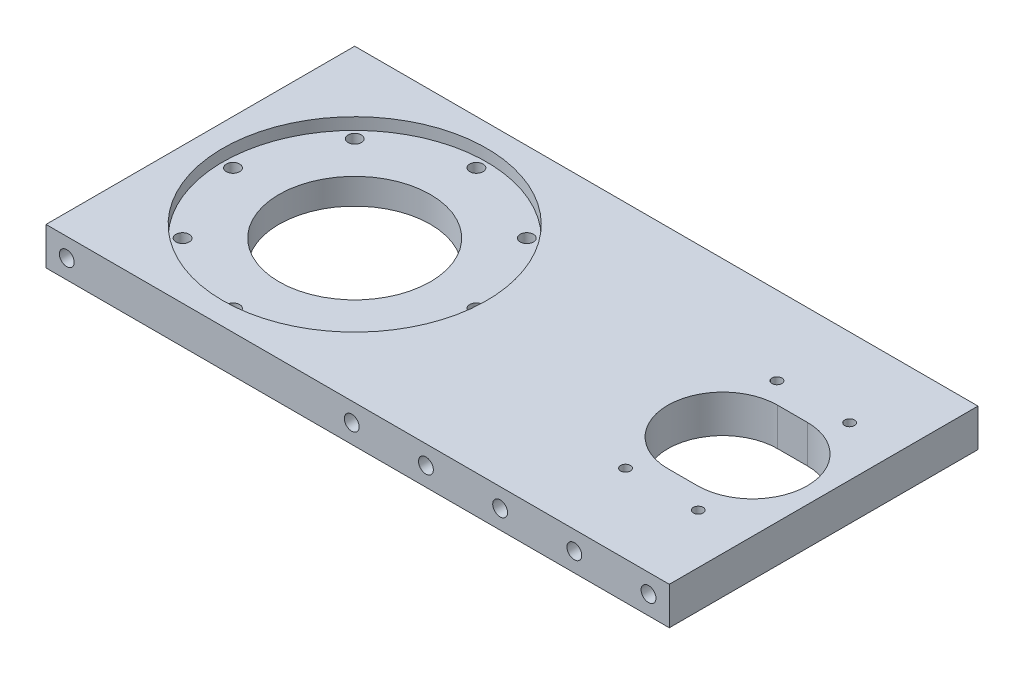
SolidWorks part; units mm, degrees
material "1060 合金"
ref_plane "前视基准面" through (0, 0, 0) normal (0, 0, 1) x (1, 0, 0)
ref_plane "上视基准面" through (0, 0, 0) normal (0, 1, 0) x (1, 0, 0)
ref_plane "右视基准面" through (0, 0, 0) normal (1, 0, 0) x (0, 0, -1)
sketch "草图1" plane through (0, 0, 0) normal (0, 1, 0) x (1, 0, 0)
  line L0 (0, 0) -> (170, 0) construction
  line L1 (170, 31.93) -> (170, -31.93)
  line L2 (15.8391, 73.3084) -> (162.1119, 41.7045)
  line L3 (15.8391, -73.3084) -> (162.1119, -41.7045)
  arc A0 (15.8391, 73.3084) -> (15.8391, -73.3084) centre (0, 0) ccw
  arc A1 (162.1119, -41.7045) -> (170, -31.93) centre (160, -31.93) ccw
  arc A2 (170, 31.93) -> (162.1119, 41.7045) centre (160, 31.93) ccw
  point P6 (170, 0)
  dimension "D1" = 150
  dimension "D4" = 20
  dimension "D5" = 20
  dimension "D2" = 170
  dimension "D3" = 63.86
extrude "凸台-拉伸1" add sketch "草图1" along normal blind 30
sketch "草图2" plane through (0, 30, 0) normal (0, 1, 0) x (1, 0, 0)
  circle A0 centre (0, 0) radius 44.45
  dimension "D1" = 88.9
extrude "切除-拉伸1" cut sketch "草图2" against normal blind 4
sketch "草图3" plane through (0, 26, 0) normal (0, 1, 0) x (1, 0, 0)
  line L0 (0, 0) -> (0, 90.3276) construction
  circle A0 centre (0, 0) radius 25.5
  circle A1 centre (0, 41) radius 2.25
  circle A2 centre (28.9914, 28.9914) radius 2.25
  circle A3 centre (41, 0) radius 2.25
  circle A4 centre (28.9914, -28.9914) radius 2.25
  circle A5 centre (0, -41) radius 2.25
  circle A6 centre (-28.9914, -28.9914) radius 2.25
  circle A7 centre (-41, 0) radius 2.25
  circle A8 centre (-28.9914, 28.9914) radius 2.25
  dimension "D1" = 51
  dimension "D3" = 4.5
  dimension "D2" = 41
  dimension "D4" = 8
extrude "切除-拉伸2" cut sketch "草图3" against normal through all contours A2 | A3 | A4 | A5 | A6 | A7 | A8 | A1 | A0
sketch "草图4" plane through (0, 30, 0) normal (0, 1, 0) x (1, 0, 0)
  line L0 (0, 0) -> (134, 0) construction
  line L1 (124, 18.5) -> (134, 18.5)
  line L2 (124, -18.5) -> (134, -18.5)
  arc A0 (134, -18.5) -> (134, 18.5) centre (134, 0) ccw
  arc A1 (124, 18.5) -> (124, -18.5) centre (124, 0) ccw
  dimension "D2" = 37
  dimension "D3" = 37
  dimension "D1" = 134
  dimension "D4" = 10
extrude "切除-拉伸3" cut sketch "草图4" against normal through all
sketch "草图5" plane through (0, 30, 0) normal (0, 1, 0) x (1, 0, 0)
  arc A0 (134, -18.5) -> (134, 18.5) centre (134, 0) ccw construction
  arc A1 (124, 18.5) -> (124, -18.5) centre (124, 0) ccw construction
  arc A2 (134, -18.5) -> (134, 18.5) centre (134, 0) ccw construction
  arc A3 (124, 18.5) -> (124, -18.5) centre (124, 0) ccw construction
  circle A4 centre (116.75, 25.5) radius 1.65
  circle A5 centre (141.25, 25.5) radius 1.65
  circle A6 centre (141.25, -25.5) radius 1.65
  circle A7 centre (116.75, -25.5) radius 1.65
  dimension "D1" = 3.3
  dimension "D2" = 3.3
  dimension "D3" = 3.3
  dimension "D4" = 3.3
  dimension "D7" = 25.5
  dimension "D5" = 7.25
  dimension "D6" = 25.5
  dimension "D8" = 7.25
  dimension "D9" = 7.25
extrude "切除-拉伸4" cut sketch "草图5" against normal through all
sketch "草图6" plane through (0, 30, 0) normal (0, 1, 0) x (1, 0, 0)
  line L0 (158, 42.5929) -> (158, -42.5929) construction
  line L2 (-52, 54.0463) -> (-52, -54.0463) construction
  line L6 (162.1119, 41.7045) -> (15.8391, 73.3084) construction
  line L7 (15.8391, -73.3084) -> (162.1119, -41.7045) construction
  line L8 (-52, 95) -> (-52, -95)
  line L9 (158, 95) -> (158, -95)
  line L10 (-52, 95) -> (158, 95)
  line L11 (-52, -95) -> (158, -95)
  line L15 (162.1119, 41.7045) -> (15.8391, 73.3084)
  line L16 (15.8391, -73.3084) -> (162.1119, -41.7045)
  line L17 (170, -31.93) -> (170, 31.93)
  line L18 (162.1119, 41.7045) -> (15.8391, 73.3084)
  line L19 (15.8391, -73.3084) -> (162.1119, -41.7045)
  line L20 (170, -31.93) -> (170, 31.93)
  arc A0 (15.8391, 73.3084) -> (15.8391, -73.3084) centre (0, 0) ccw construction
  arc A6 (170, 31.93) -> (162.1119, 41.7045) centre (160, 31.93) ccw
  arc A7 (15.8391, 73.3084) -> (15.8391, -73.3084) centre (0, 0) ccw
  arc A8 (162.1119, -41.7045) -> (170, -31.93) centre (160, -31.93) ccw
  arc A9 (170, 31.93) -> (162.1119, 41.7045) centre (160, 31.93) ccw
  arc A10 (15.8391, 73.3084) -> (15.8391, -73.3084) centre (0, 0) ccw
  arc A11 (162.1119, -41.7045) -> (170, -31.93) centre (160, -31.93) ccw
  point P8 (-52, 0)
  point P13 (158, 0)
  line M26 (162.1119, 41.7045) -> (15.8391, 73.3084)
  arc M27 (15.8391, 73.3084) -> (15.8391, -73.3084) centre (0, 0) ccw
  line M28 (15.8391, -73.3084) -> (162.1119, -41.7045)
  dimension "D3" = 190
  dimension "D1" = 210
  dimension "D2" = 52
  dimension "D4" = 190
  dimension "D5" = 0
extrude "凸台-拉伸2" add sketch "草图6" against normal blind 30 contours L10 L8 L9 M27 M26 | L8 L11 L9 M28 M27
sketch "草图7" plane through (0, 30, 0) normal (0, 1, 0) x (1, 0, 0)
  line L0 (-52, 54.0463) -> (-52, -54.0463)
  line L1 (158, 42.5929) -> (158, -42.5929)
  line L9 (162.1119, 41.7045) -> (158, 42.5929)
  line L10 (158, 42.5929) -> (158, 95)
  line L11 (158, 95) -> (-52, 95)
  line L12 (-52, 95) -> (-52, 54.0463)
  line L13 (-52, -54.0463) -> (-52, -95)
  line L14 (-52, -95) -> (158, -95)
  line L15 (158, -95) -> (158, -42.5929)
  line L16 (158, -42.5929) -> (162.1119, -41.7045)
  line L17 (170, -31.93) -> (170, 31.93)
  line L18 (162.1119, 41.7045) -> (158, 42.5929)
  line L21 (-52, 95) -> (-52, 54.0463)
  line L25 (158, -42.5929) -> (162.1119, -41.7045)
  line L26 (170, -31.93) -> (170, 31.93)
  arc A3 (170, 31.93) -> (162.1119, 41.7045) centre (160, 31.93) ccw
  arc A4 (-52, 54.0463) -> (-52, -54.0463) centre (0, 0) ccw
  arc A5 (162.1119, -41.7045) -> (170, -31.93) centre (160, -31.93) ccw
  arc A6 (170, 31.93) -> (162.1119, 41.7045) centre (160, 31.93) ccw
  arc A7 (-52, 54.0463) -> (-52, -54.0463) centre (0, 0) ccw
  arc A8 (162.1119, -41.7045) -> (170, -31.93) centre (160, -31.93) ccw
  arc M22 (170, 31.93) -> (162.1119, 41.7045) centre (160, 31.93) ccw
  line M23 (162.1119, 41.7045) -> (158, 42.5929)
  arc M27 (-52, 54.0463) -> (-52, -54.0463) centre (0, 0) ccw
  line M31 (158, -42.5929) -> (162.1119, -41.7045)
  arc M32 (162.1119, -41.7045) -> (170, -31.93) centre (160, -31.93) ccw
  line M33 (170, -31.93) -> (170, 31.93)
  dimension "D1" = 0
extrude "切除-拉伸5" cut sketch "草图7" against normal through all contours L0 M27 | L1 M23 M31 M32 M33 M22
sketch "草图9" plane through (-52, 0, 0) normal (-1, 0, 0) x (0, 0, 1)
  line L0 (-95, 20) -> (-60, 10.6218)
  line L1 (-95, 30) -> (95, 30) construction
  line L3 (-60, 10.6218) -> (-60, 30)
  line L5 (-95, 0) -> (-95, 30) construction
  line L7 (-95, 20) -> (-95, 30)
  line L8 (-95, 30) -> (-60, 30)
  dimension "D1" = 15
  dimension "D3" = 19.3782
  dimension "D4" = 35
  dimension "D5" = 10
extrude "切除-拉伸7" cut sketch "草图9" against normal through all contours L8 L3 L0 L7
sketch "草图8" plane through (-52, 0, 0) normal (-1, 0, 0) x (0, 0, 1)
  line L0 (0, 0) -> (52, 0)
  line L1 (-95, 0) -> (95, 0) construction
  line L2 (52, 0) -> (52, 17.3)
  line L3 (52, 17.3) -> (-52, 17.3)
  line L4 (-52, 17.3) -> (-52, 0)
  line L5 (-52, 0) -> (0, 0)
  line L6 (-60, 30) -> (95, 30) construction
  dimension "D1" = 52
  dimension "D2" = 52
  dimension "D3" = 12.7
sketch "草图10" plane through (-52, 0, 0) normal (-1, 0, 0) x (0, 0, 1)
  line L0 (-95, 12.7531) -> (-47.4049, 0) construction
  line L1 (-95, 0) -> (-95, 20) construction
  line L2 (-95, 0) -> (95, 0) construction
  line L3 (-95, 20) -> (-60, 10.6218) construction
  line L6 (-95, 12.7531) -> (-52, 1.2313)
  line L7 (-52, 1.2313) -> (-52, 0)
  line L8 (-95, 12.7531) -> (-95, 0)
  line L9 (-95, 0) -> (-52, 0)
  line L10 (-52, 17.3) -> (-52, 0) construction
  dimension "D1" = 7
extrude "切除-拉伸8" cut sketch "草图10" against normal through all
extrude "切除-拉伸9" cut sketch "草图8" against normal through all
fillet "圆角1" radius 5 1 edges at (53, 10.6218, -60)
sketch "草图11" plane through (-52, 0, 0) normal (-1, 0, 0) x (0, 0, 1)
  line L0 (-95, 12.7531) -> (-93.1883, 19.5145)
  line L1 (-95, 20) -> (-66.2941, 12.3083) construction
  line L2 (-93.1883, 19.5145) -> (-95, 20)
  line L3 (-95, 20) -> (-95, 12.7531)
extrude "切除-拉伸10" cut sketch "草图11" against normal through all
sketch "草图12" plane through (-52, 0, 0) normal (-1, 0, 0) x (0, 0, 1)
  line L0 (-93.1883, 19.5145) -> (-60, 30)
  line L10 (-93.1883, 19.5145) -> (-95, 12.7531)
  line L11 (-95, 12.7531) -> (-52, 1.2313)
  line L12 (-52, 1.2313) -> (-52, 17.3)
  line L13 (-52, 17.3) -> (52, 17.3)
  line L14 (52, 17.3) -> (52, 0)
  line L15 (52, 0) -> (95, 0)
  line L16 (95, 0) -> (95, 30)
  line L17 (95, 30) -> (-60, 30)
  line L18 (-60, 30) -> (-60, 17.1379)
  line L19 (-66.2941, 12.3083) -> (-93.1883, 19.5145)
  line L28 (-60, 30) -> (-60, 17.1379)
  line L29 (-66.2941, 12.3083) -> (-93.1883, 19.5145)
  arc A1 (-66.2941, 12.3083) -> (-60, 17.1379) centre (-65, 17.1379) ccw
  arc A2 (-66.2941, 12.3083) -> (-60, 17.1379) centre (-65, 17.1379) ccw
  dimension "D1" = 0
extrude "凸台-拉伸3" add sketch "草图12" against normal blind 5
sketch "草图13" plane through (158, 0, 0) normal (1, 0, 0) x (0, 0, -1)
  line L3 (66.2941, 12.3083) -> (93.1883, 19.5145)
  line L4 (93.1883, 19.5145) -> (60, 30)
  line L5 (60, 30) -> (60, 17.1379)
  line L6 (66.2941, 12.3083) -> (93.1883, 19.5145)
  line L7 (93.1883, 19.5145) -> (60, 30)
  line L8 (60, 30) -> (60, 17.1379)
  arc A1 (60, 17.1379) -> (66.2941, 12.3083) centre (65, 17.1379) ccw
  arc A2 (60, 17.1379) -> (66.2941, 12.3083) centre (65, 17.1379) ccw
  dimension "D1" = 0
extrude "凸台-拉伸4" add sketch "草图13" against normal blind 5
sketch "草图14" plane through (0, -5.0897, -1.3638) normal (0, 0.9659, 0.2588) x (1, 0, 0)
  line L0 (153, 67.2208) -> (153, 95.0637) construction
  line L3 (153, 95.0637) -> (-47, 95.0637) construction
  circle A0 centre (-27, 82.0637) radius 4.25
  circle A1 centre (23, 82.0637) radius 4.25
  circle A2 centre (83, 82.0637) radius 4.25
  circle A3 centre (133, 82.0637) radius 4.25
  dimension "D1" = 8.5
  dimension "D2" = 160
  dimension "D3" = 20
  dimension "D4" = 50
  dimension "D5" = 50
  dimension "D6" = 13
extrude "切除-拉伸11" cut sketch "草图14" against normal through all
sketch "草图16" plane through (-52, 0, 0) normal (-1, 0, 0) x (0, 0, 1)
  line L0 (-60, 30) -> (95, 30) construction
  line L1 (95, 0) -> (52, 0)
  line L2 (95, 0) -> (95, 30)
  line L3 (95, 30) -> (52, 30)
  line L4 (52, 0) -> (52, 30)
extrude "切除-拉伸12" cut sketch "草图16" against normal through all
ref_plane "基准面1" through (0, -11.8512, -3.1755) normal (0, -0.9659, -0.2588) x (-1, 0, 0)
sketch "草图18" plane through (0, 30, 0) normal (0, 1, 0) x (1, 0, 0)
  line L1 (-52, -52) -> (158, -52)
  line L2 (-52, -52) -> (-52, -57)
  line L3 (-52, -57) -> (158, -57)
  line L4 (158, -52) -> (158, -57)
  dimension "D1" = 5
extrude "凸台-拉伸7" add sketch "草图18" against normal up to surface (56.6355 mm away) up to plane "基准面1"
sketch "草图19" plane through (-52, 0, 0) normal (-1, 0, 0) x (0, 0, 1)
  line L0 (57, -27.9752) -> (90.1883, -36.868)
  line L1 (90.1883, -36.868) -> (92, -30.1065)
  line L2 (92, -30.1065) -> (57, -20.7283)
  line L3 (57, -27.9752) -> (57, 30) construction
  line L4 (57, -20.7283) -> (57, -27.9752)
  line L5 (52, -26.6355) -> (57, -27.9752) construction
  dimension "D1" = 7
  dimension "D2" = 40
extrude "凸台-拉伸8" add sketch "草图19" against normal up to surface (210 mm away) up to face at (158, 8.1654, -14.9098)
sketch "草图20" plane through (-52, 0, 0) normal (-1, 0, 0) x (0, 0, 1)
  line L0 (92, -30.1065) -> (57, -20.7283) construction
  line L1 (57, -20.7283) -> (57, 30) construction
  line L2 (92, -30.1065) -> (57, -20.7283)
  line L3 (57, -20.7283) -> (57, 30)
  line L4 (57, 30) -> (92, -30.1065)
extrude "凸台-拉伸9" add sketch "草图20" against normal blind 5
sketch "草图21" plane through (158, 0, 0) normal (1, 0, 0) x (0, 0, -1)
  line L3 (-57, 30) -> (-92, -30.1065)
  line L4 (-92, -30.1065) -> (-57, -20.7283)
  line L5 (-57, -20.7283) -> (-57, 30)
  line L6 (-57, 30) -> (-92, -30.1065)
  line L7 (-92, -30.1065) -> (-57, -20.7283)
  line L8 (-57, -20.7283) -> (-57, 30)
  dimension "D1" = 0
extrude "凸台-拉伸10" add sketch "草图21" against normal blind 5
sketch "草图22" plane through (0, -5.0897, -1.3638) normal (0, 0.9659, 0.2588) x (1, 0, 0)
  line L0 (-47, -96.6573) -> (-47, -47.2932) construction
  line L2 (153, -96.6573) -> (153, -60.4226) construction
  circle A0 centre (-27, -77.9363) radius 4.25
  circle A1 centre (23, -69.9363) radius 4.25
  circle A2 centre (83, -69.9363) radius 4.25
  circle A3 centre (133, -77.9363) radius 4.25
  circle A4 centre (133, 82.0637) radius 4.25 construction
  circle A5 centre (-27, 82.0637) radius 4.25 construction
  circle A6 centre (23, 82.0637) radius 4.25 construction
  circle A7 centre (83, 82.0637) radius 4.25 construction
  dimension "D1" = 8.5
  dimension "D7" = 152
  dimension "D6" = 152
  dimension "D8" = 50
  dimension "D4" = 160
  dimension "D5" = 160
  dimension "D2" = 20
  dimension "D3" = 20
  dimension "D9" = 50
extrude "切除-拉伸13" cut sketch "草图22" against normal through all
fillet "圆角2" radius 5 1 edges at (53, -20.7283, 57)
sketch "草图23" plane through (-52, 0, 0) normal (-1, 0, 0) x (0, 0, 1)
  line L0 (-52, 17.3) -> (-52, 43.8054)
  line L1 (-52, 43.8054) -> (-100.3, 43.8054)
  line L2 (-100.3, 43.8054) -> (-100.3, -10.9962)
  line L3 (-100.3, -10.9962) -> (-52, -10.9962)
  line L4 (-52, -10.9962) -> (-52, 17.3)
  line L5 (52, -26.6355) -> (52, 17.3) construction
  line L6 (52, 44.9839) -> (106.139, 44.9839)
  line L7 (52, 44.9839) -> (52, -48.7091)
  line L8 (52, -48.7091) -> (106.139, -48.7091)
  line L9 (106.139, 44.9839) -> (106.139, -48.7091)
extrude "切除-拉伸16" cut sketch "草图23" against normal through all contours L7 L6 L9 L8 | L4 L0 L1 L2 L3
sketch "草图24" plane through (0, 0, -52) normal (0, 0, -1) x (-1, 0, 0)
  line L0 (-158, 17.3) -> (-158, 30) construction
  line L1 (52, 30) -> (-158, 30) construction
  line L2 (52, 17.3) -> (52, 30) construction
  circle A0 centre (-126, 23.65) radius 2.5
  circle A1 centre (-101, 23.65) radius 2.5
  circle A2 centre (-151, 23.65) radius 2.5
  circle A3 centre (45, 23.65) radius 2.5
  circle A4 centre (-76, 23.65) radius 2.5
  circle A5 centre (-51, 23.65) radius 2.5
  dimension "D1" = 5
  dimension "D2" = 7
  dimension "D3" = 6.35
  dimension "D4" = 25
  dimension "D5" = 6.35
  dimension "D6" = 25
  dimension "D7" = 6.35
  dimension "D8" = 25
  dimension "D9" = 6.35
  dimension "D10" = 25
  dimension "D11" = 6.35
  dimension "D14" = 7
  dimension "D15" = 6.35
extrude "切除-拉伸17" cut sketch "草图24" against normal blind 20
sketch "草图25" plane through (0, 0, 52) normal (0, 0, 1) x (1, 0, 0)
  line L0 (158, 30) -> (158, 17.3) construction
  line L1 (158, 30) -> (-52, 30) construction
  line L2 (-52, 30) -> (-52, 17.3) construction
  circle A0 centre (151, 23.65) radius 2.5
  circle A1 centre (126, 23.65) radius 2.5
  circle A2 centre (101, 23.65) radius 2.5
  circle A3 centre (76, 23.65) radius 2.5
  circle A4 centre (51, 23.65) radius 2.5
  circle A6 centre (-45, 23.65) radius 2.5
  dimension "D1" = 5
  dimension "D2" = 7
  dimension "D3" = 25
  dimension "D4" = 6.35
  dimension "D5" = 6.35
  dimension "D6" = 6.35
  dimension "D7" = 25
  dimension "D8" = 25
  dimension "D9" = 25
  dimension "D10" = 6.35
  dimension "D11" = 6.35
  dimension "D12" = 6.35
  dimension "D13" = 7
extrude "切除-拉伸18" cut sketch "草图25" against normal blind 20
sketch "草图26" plane through (0, 17.3, 0) normal (0, -1, 0) x (1, 0, 0)
  circle A0 centre (0, 41) radius 4
  circle A4 centre (28.9914, 28.9914) radius 4
  circle A5 centre (41, 0) radius 4
  circle A6 centre (28.9914, -28.9914) radius 4
  circle A7 centre (0, -41) radius 4
  circle A8 centre (-28.9914, -28.9914) radius 4
  circle A9 centre (-41, 0) radius 4
  circle A10 centre (-28.9914, 28.9914) radius 4
  dimension "D1" = 8
  dimension "D2" = 8
extrude "切除-拉伸19" cut sketch "草图26" against normal blind 3
